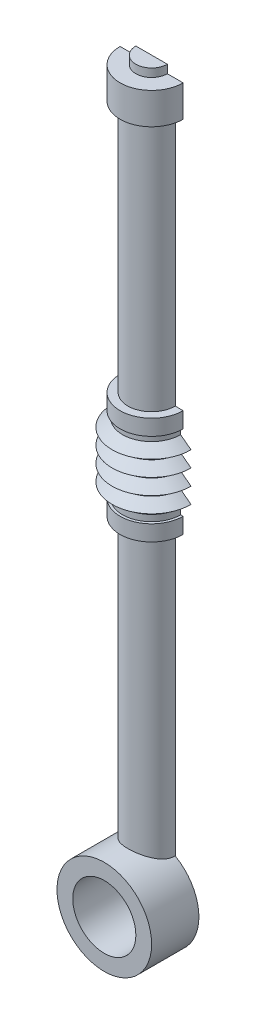
SolidWorks part; units mm, degrees
ref_plane "Front Plane" through (0, 0, 0) normal (0, 0, 1) x (1, 0, 0)
ref_plane "Top Plane" through (0, 0, 0) normal (0, 1, 0) x (1, 0, 0)
ref_plane "Right Plane" through (0, 0, 0) normal (1, 0, 0) x (0, 0, -1)
sketch "Sketch1" plane through (0, 0, 0) normal (0, 0, 1) x (1, 0, 0)
  circle A0 centre (0, 0) radius 3.175
  circle A1 centre (0, 0) radius 4.7625
  dimension "D1" = 6.35
  dimension "D2" = 1.5875
extrude "Boss-Extrude1" add sketch "Sketch1" along normal blind 4.7625 and the other way blind 2.3813
ref_plane "Plane1" through (0, 4.7625, 0) normal (0, 1, 0) x (1, 0, 0)
sketch "Sketch2" plane through (0, 4.7625, 0) normal (0, 1, 0) x (1, 0, 0)
  line L1 (4.7625, 2.3813) -> (-4.7625, 2.3813) construction
  circle A0 centre (0, 0) radius 2.3813
  dimension "D1" = 4.7625
extrude "Boss-Extrude2" add sketch "Sketch2" along normal blind 28.575 and the other way up to surface other way up to face at (4.7625, 0, -2.3813)
sketch "Sketch3" plane through (0, 0, 0) normal (1, 0, 0) x (0, 0, -1)
  line L0 (-2.921, 34.1313) -> (-2.921, 34.7662)
  line L1 (0, 32.5438) -> (-3.175, 32.5438)
  line L2 (0, 32.5438) -> (0, 34.1313)
  line L3 (0, 34.1313) -> (-3.175, 34.1313)
  line L4 (-3.175, 32.5438) -> (-3.175, 34.1313)
  line L5 (-2.921, 34.7662) -> (-3.9688, 35.56)
  line L6 (-3.9688, 35.56) -> (-2.921, 36.3537)
  line L7 (2.3813, 33.3375) -> (-2.3813, 33.3375) construction
  line L8 (-2.3813, 33.3375) -> (-2.3813, 4.7625) construction
  line L9 (-2.3813, 33.3375) -> (-2.3813, 4.7625) construction
  line L10 (-2.921, 36.3537) -> (-3.9688, 37.1475)
  line L11 (-3.9688, 37.1475) -> (-2.921, 37.9412)
  line L12 (-2.921, 37.9412) -> (-3.9688, 38.735)
  line L13 (-3.9688, 38.735) -> (-2.921, 39.5287)
  line L14 (-2.921, 39.5287) -> (-3.9687, 40.3225)
  line L15 (-3.9687, 40.3225) -> (-2.921, 41.1162)
  line L16 (-2.921, 41.1162) -> (-2.921, 41.7512)
  line L17 (-2.921, 41.7512) -> (-3.175, 41.7512)
  line L18 (-3.175, 41.7512) -> (-3.175, 43.3387)
  line L19 (-3.175, 43.3387) -> (0, 43.3387)
  line L20 (0, 43.3387) -> (0, 34.1313)
  line L21 (0, 34.1313) -> (0.014, 34.1171)
  dimension "D1" = 0.635
  dimension "D2" = 1.5875
  dimension "D3" = 0.7937
  dimension "D4" = 0.7937
  dimension "D5" = 2.3813
  dimension "D6" = 1.5875
  dimension "D7" = 0.7937
  dimension "D8" = 0.254
  dimension "D9" = 0.7937
  dimension "D10" = 1.5875
revolve "Revolve1" add sketch "Sketch3" angle 360 about L2
sketch "Sketch4" plane through (0, 43.3387, 0) normal (0, 1, 0) x (1, 0, 0)
  circle A0 centre (0, 0) radius 2.3813
  dimension "D1" = 4.7625
extrude "Boss-Extrude3" add sketch "Sketch4" along normal blind 25.4
sketch "Sketch5" plane through (0, 68.7387, 0) normal (0, 1, 0) x (1, 0, 0)
  circle A0 centre (0, 0) radius 3.175
  dimension "D1" = 6.35
extrude "Boss-Extrude4" add sketch "Sketch5" along normal blind 3.175
sketch "Sketch6" plane through (0, 71.9137, 0) normal (0, 1, 0) x (1, 0, 0)
  circle A0 centre (0, 0) radius 1.5875
  dimension "D1" = 3.175
extrude "Boss-Extrude5" add sketch "Sketch6" along normal blind 0.8318
sketch "Sketch7" plane through (0, 0, 0) normal (0, 0, 1) x (1, 0, 0)
  line L1 (-7.1402, 75.337) -> (8.3945, 75.337)
  line L2 (-7.1402, 75.337) -> (-7.1402, -6.4855)
  line L3 (-7.1402, -6.4855) -> (8.3945, -6.4855)
  line L4 (8.3945, 75.337) -> (8.3945, -6.4855)
extrude "Cut-Extrude1" cut sketch "Sketch7" against normal through all
